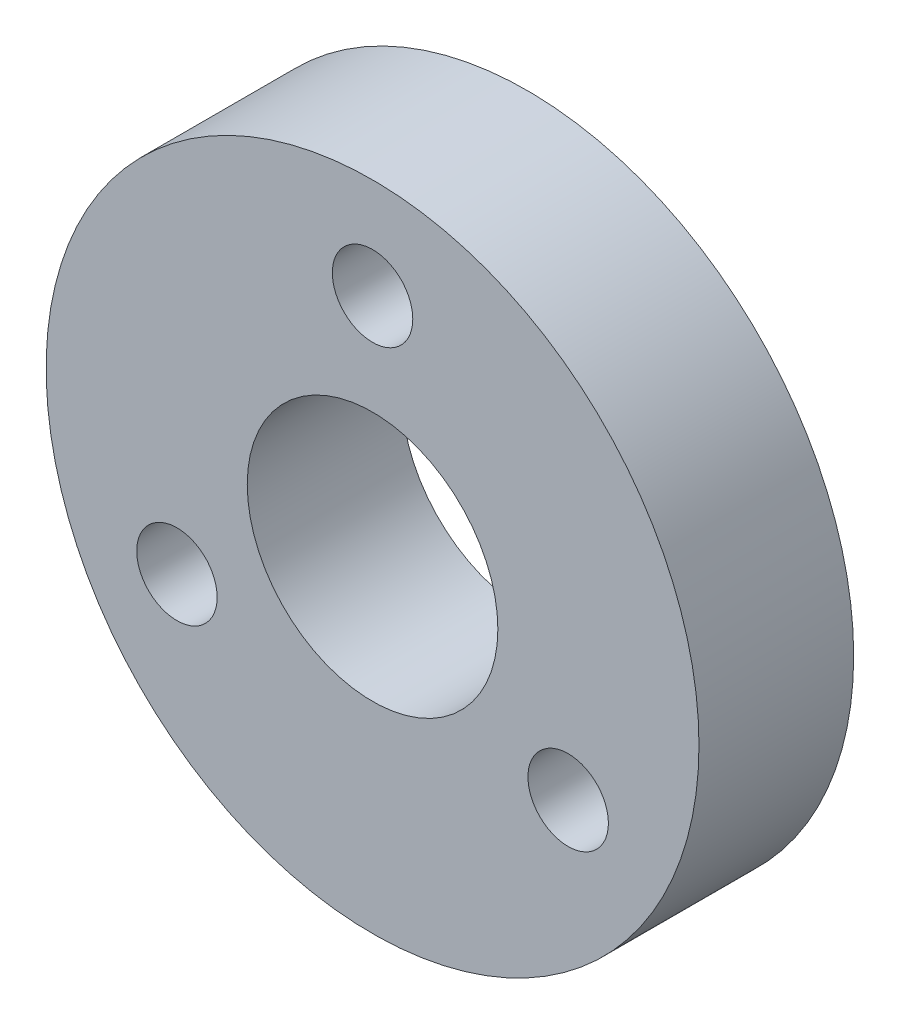
SolidWorks part; units mm, degrees
ref_plane "Front Plane" through (0, 0, 0) normal (0, 0, 1) x (1, 0, 0)
ref_plane "Top Plane" through (0, 0, 0) normal (0, 1, 0) x (1, 0, 0)
ref_plane "Right Plane" through (0, 0, 0) normal (1, 0, 0) x (0, 0, -1)
sketch "Sketch1" plane through (0, 0, 0) normal (0, 0, 1) x (1, 0, 0)
  line L0 (0, 0) -> (0, 9.4773) construction
  circle A0 centre (0, 0) radius 4.05
  circle A1 centre (0, 0) radius 10.55
  circle A2 centre (0, 7.3) radius 3.25 construction
  circle A3 centre (0, 7.3) radius 1.3
  circle A4 centre (6.322, -3.65) radius 1.3
  circle A5 centre (-6.322, -3.65) radius 1.3
  circle A6 centre (0, 0) radius 7.3 construction
  point P10 (0, 0)
  point P14 (0, 0)
  point P15 (0, 0)
  dimension "D1" = 8.1
  dimension "D3" = 6.5
  dimension "D4" = 2.6
  dimension "D5" = 3
extrude "Boss-Extrude1" add sketch "Sketch1" along normal blind 5
